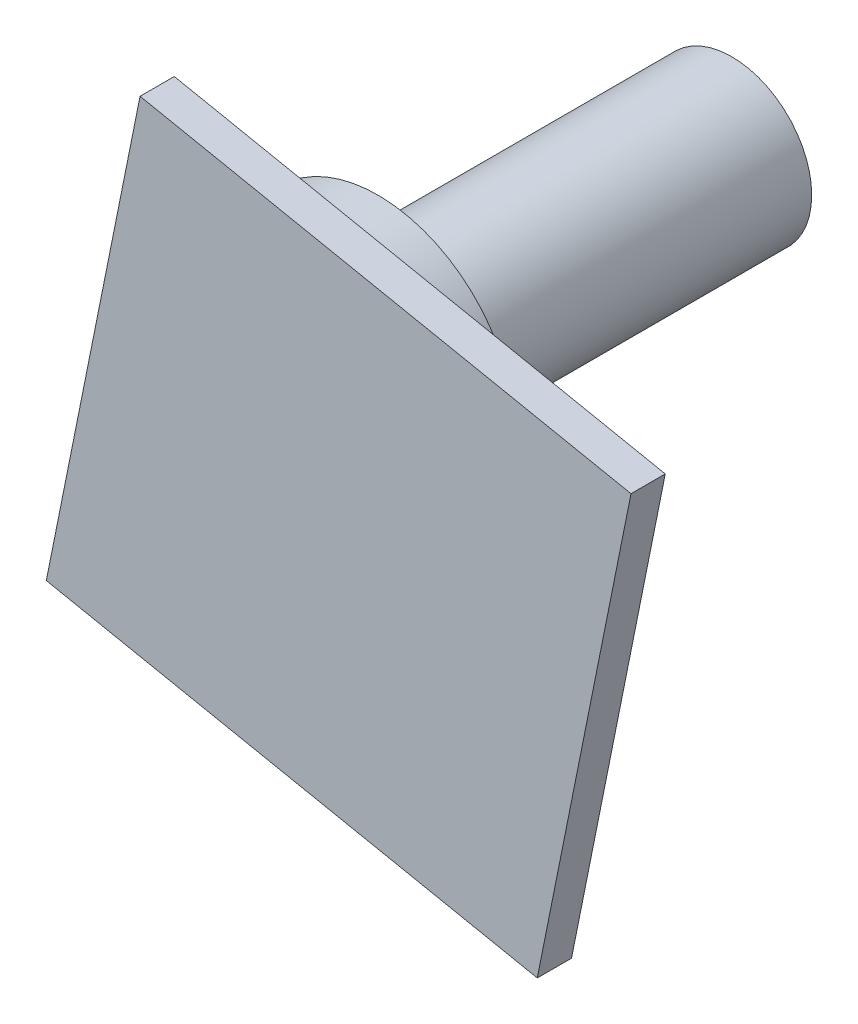
SolidWorks part; units mm, degrees
ref_plane "前视基准面" through (0, 0, 0) normal (0, 0, 1) x (1, 0, 0)
ref_plane "上视基准面" through (0, 0, 0) normal (0, 1, 0) x (1, 0, 0)
ref_plane "右视基准面" through (0, 0, 0) normal (1, 0, 0) x (0, 0, -1)
other "Configuration Table"
sketch "草图1" plane through (0, 0, 0) normal (0, 0, 1) x (1, 0, 0)
  circle A0 centre (-86.6066, -63.7835) radius 7
extrude "凸台-拉伸1" add sketch "草图1" along normal blind 34
sketch "草图2" plane through (0, 0, 34) normal (0, 0, 1) x (1, 0, 0)
  circle A0 centre (-86.6066, -63.7835) radius 12
extrude "凸台-拉伸2" add sketch "草图2" against normal blind 3 and the other way blind 2
sketch "草图3" plane through (0, 0, 36) normal (0, 0, 1) x (1, 0, 0)
  line L0 (-110.1056, -28.4593) -> (-40.7849, -42.3949) construction
  line L3 (-99.4536, -46.7086) -> (-56.4369, -55.3563)
  line L4 (-99.4536, -46.7086) -> (-107.6666, -87.5628)
  line L5 (-56.4369, -55.3563) -> (-64.6498, -96.2105)
  line L6 (-107.6666, -87.5628) -> (-64.6498, -96.2105)
extrude "凸台-拉伸4" add sketch "草图3" along normal blind 3
